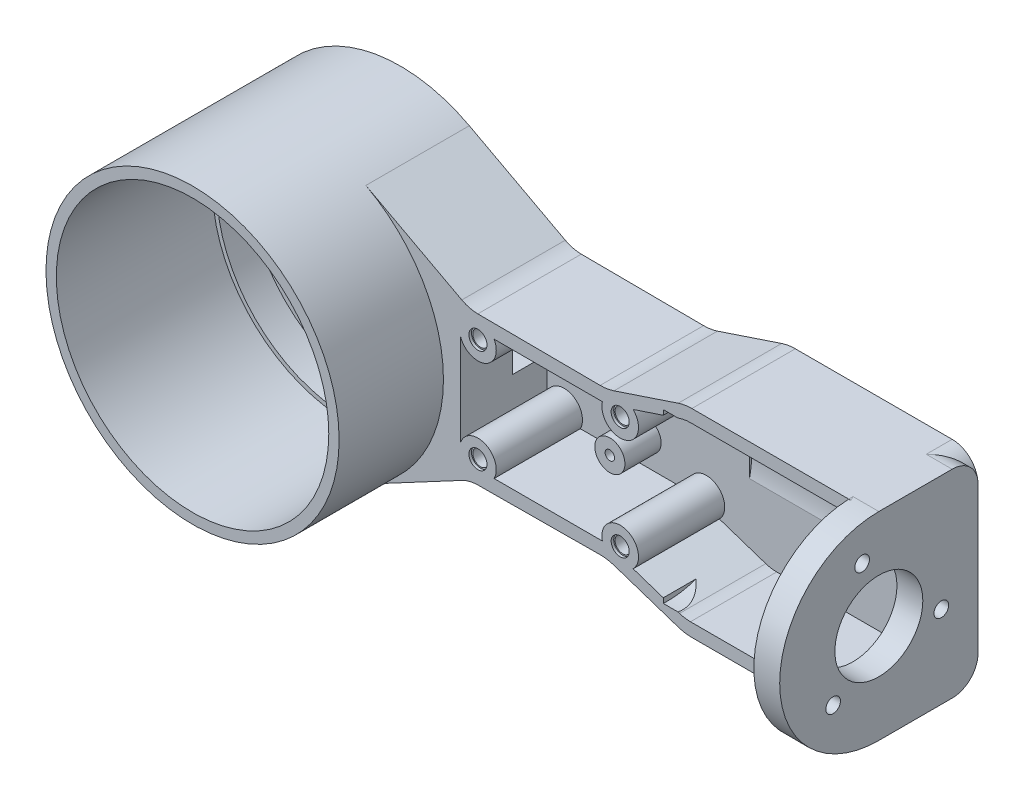
SolidWorks part; units mm, degrees
ref_plane "前视基准面" through (0, 0, 0) normal (0, 0, 1) x (1, 0, 0)
ref_plane "上视基准面" through (0, 0, 0) normal (0, 1, 0) x (1, 0, 0)
ref_plane "右视基准面" through (0, 0, 0) normal (1, 0, 0) x (0, 0, -1)
other "Configuration Table"
sketch "草图1" plane through (0, 0, 0) normal (0, 0, 1) x (1, 0, 0)
  line L0 (16, -30) -> (38.2587, -18.1287)
  line L1 (41.9734, -17.1877) -> (70.3452, -17.0103)
  line L2 (73.5699, -17.5233) -> (88.4605, -22.4868)
  line L3 (91.6228, -23) -> (128, -23)
  line L4 (134, -17) -> (134, 17)
  line L5 (128, 23) -> (91.6228, 23)
  line L6 (88.4605, 22.4868) -> (73.5699, 17.5233)
  line L7 (70.3452, 17.0103) -> (41.9734, 17.1877)
  line L8 (38.2587, 18.1287) -> (16, 30)
  arc A0 (38.2587, -18.1287) -> (41.9734, -17.1877) centre (42.0234, -25.1875) cw
  arc A1 (70.3452, -17.0103) -> (73.5699, -17.5233) centre (70.4077, -27.0101) cw
  arc A2 (88.4605, -22.4868) -> (91.6228, -23) centre (91.6228, -13) ccw
  arc A3 (128, -23) -> (134, -17) centre (128, -17) ccw
  arc A4 (134, 17) -> (128, 23) centre (128, 17) ccw
  arc A5 (91.6228, 23) -> (88.4605, 22.4868) centre (91.6228, 13) ccw
  arc A6 (73.5699, 17.5233) -> (70.3452, 17.0103) centre (70.4077, 27.0101) cw
  arc A7 (41.9734, 17.1877) -> (38.2587, 18.1287) centre (42.0234, 25.1875) cw
  arc A8 (16, 30) -> (16, -30) centre (0, 0) ccw
extrude "Single_flat_print_face_roof_T4" add sketch "草图1" along normal blind 4
ref_plane "Plane_z_4_1" through (0, 0, 4) normal (0, 0, 1) x (1, 0, 0)
sketch "草图2" plane through (0, 0, 4) normal (0, 0, 1) x (1, 0, 0)
  circle A0 centre (0, 0) radius 34
extrude "Motor_roof_total_T5" add sketch "草图2" along normal blind 1
ref_plane "Plane_z_4_2" through (0, 0, 4) normal (0, 0, 1) x (1, 0, 0)
sketch "草图3" plane through (0, 0, 4) normal (0, 0, 1) x (1, 0, 0)
  line L0 (16, -30) -> (38.2587, -18.1287)
  line L1 (41.9734, -17.1877) -> (70.3452, -17.0103)
  line L2 (73.5699, -17.5233) -> (88.4605, -22.4868)
  line L3 (91.6228, -23) -> (128, -23)
  line L4 (134, -17) -> (134, 17)
  line L5 (128, 23) -> (91.6228, 23)
  line L6 (88.4605, 22.4868) -> (73.5699, 17.5233)
  line L7 (70.3452, 17.0103) -> (41.9734, 17.1877)
  line L8 (38.2587, 18.1287) -> (16, 30)
  arc A0 (38.2587, -18.1287) -> (41.9734, -17.1877) centre (42.0234, -25.1875) cw
  arc A1 (70.3452, -17.0103) -> (73.5699, -17.5233) centre (70.4077, -27.0101) cw
  arc A2 (88.4605, -22.4868) -> (91.6228, -23) centre (91.6228, -13) ccw
  arc A3 (128, -23) -> (134, -17) centre (128, -17) ccw
  arc A4 (134, 17) -> (128, 23) centre (128, 17) ccw
  arc A5 (91.6228, 23) -> (88.4605, 22.4868) centre (91.6228, 13) ccw
  arc A6 (73.5699, 17.5233) -> (70.3452, 17.0103) centre (70.4077, 27.0101) cw
  arc A7 (41.9734, 17.1877) -> (38.2587, 18.1287) centre (42.0234, 25.1875) cw
  arc A8 (16, 30) -> (16, -30) centre (0, 0) ccw
extrude "Arm_shell_blank_toZ24" add sketch "草图3" along normal blind 20
ref_plane "Plane_z_24_3" through (0, 0, 24) normal (0, 0, 1) x (1, 0, 0)
sketch "草图4" plane through (0, 0, 24) normal (0, 0, 1) x (1, 0, 0)
  circle A0 centre (0, 0) radius 30.6
extrude "Rotor_cup_ID61p2_roof_T5" cut sketch "草图4" against normal blind 19
ref_plane "Plane_z_24_4" through (0, 0, 24) normal (0, 0, 1) x (1, 0, 0)
sketch "草图5" plane through (0, 0, 24) normal (0, 0, 1) x (1, 0, 0)
  line L0 (41, -14) -> (70.7018, -14)
  line L1 (73.2316, -14.4105) -> (88.7684, -19.5895)
  line L2 (91.2982, -20) -> (125, -20)
  line L3 (128, -17) -> (128, 17)
  line L4 (125, 20) -> (91.2982, 20)
  line L5 (88.7684, 19.5895) -> (73.2316, 14.4105)
  line L6 (70.7018, 14) -> (41, 14)
  line L7 (38, 11) -> (38, -11)
  arc A0 (38, -11) -> (41, -14) centre (41, -11) ccw
  arc A1 (70.7018, -14) -> (73.2316, -14.4105) centre (70.7018, -22) cw
  arc A2 (88.7684, -19.5895) -> (91.2982, -20) centre (91.2982, -12) ccw
  arc A3 (125, -20) -> (128, -17) centre (125, -17) ccw
  arc A4 (128, 17) -> (125, 20) centre (125, 17) ccw
  arc A5 (91.2982, 20) -> (88.7684, 19.5895) centre (91.2982, 12) ccw
  arc A6 (73.2316, 14.4105) -> (70.7018, 14) centre (70.7018, 22) cw
  arc A7 (41, 14) -> (38, 11) centre (41, 11) ccw
extrude "Bottom_service_bay_roof_T4" cut sketch "草图5" against normal blind 20
ref_plane "Plane_z_24_5" through (0, 0, 24) normal (0, 0, 1) x (1, 0, 0)
sketch "草图6" plane through (0, 0, 24) normal (0, 0, 1) x (1, 0, 0)
  circle A0 centre (0, 0) radius 34
  circle A1 centre (0, 0) radius 30.6
extrude "Rotor_wrap_skirt_OD68_toZ48p2" add sketch "草图6" along normal blind 24.2
ref_plane "Plane_z_48.2_6" through (0, 0, 48.2) normal (0, 0, 1) x (1, 0, 0)
sketch "草图7" plane through (0, 0, 48.2) normal (0, 0, 1) x (1, 0, 0)
  circle A0 centre (0, 0) radius 31.6
extrude "Thin_lower_shroud_T2p4_radial_clearance1p8" cut sketch "草图7" against normal blind 36.2
ref_plane "Plane_z_5_7" through (0, 0, 5) normal (0, 0, 1) x (1, 0, 0)
sketch "草图8" plane through (0, 0, 5) normal (0, 0, 1) x (1, 0, 0)
  circle A0 centre (8.8388, 8.8388) radius 5
  circle A1 centre (-8.8388, 8.8388) radius 5
  circle A2 centre (-8.8388, -8.8388) radius 5
  circle A3 centre (8.8388, -8.8388) radius 5
extrude "Four_motor_mount_bosses_toZ12" add sketch "草图8" along normal blind 7
ref_plane "Plane_z_12_8" through (0, 0, 12) normal (0, 0, 1) x (1, 0, 0)
sketch "草图9" plane through (0, 0, 12) normal (0, 0, 1) x (1, 0, 0)
  line L0 (-2, -3) -> (42, -3)
  line L1 (43, -2) -> (43, 2)
  line L2 (42, 3) -> (-2, 3)
  line L3 (-3, 2) -> (-3, -2)
  arc A0 (-3, -2) -> (-2, -3) centre (-2, -2) ccw
  arc A1 (42, -3) -> (43, -2) centre (42, -2) ccw
  arc A2 (43, 2) -> (42, 3) centre (42, 2) ccw
  arc A3 (-2, 3) -> (-3, 2) centre (-2, 2) ccw
extrude "Straight_six_D1_wire_channel_W6_H7" cut sketch "草图9" against normal blind 7
ref_plane "Plane_z_12_9" through (0, 0, 12) normal (0, 0, 1) x (1, 0, 0)
sketch "草图10" plane through (0, 0, 12) normal (0, 0, 1) x (1, 0, 0)
  circle A0 centre (8.8388, 8.8388) radius 1.7
  circle A1 centre (-8.8388, 8.8388) radius 1.7
  circle A2 centre (-8.8388, -8.8388) radius 1.7
  circle A3 centre (8.8388, -8.8388) radius 1.7
extrude "Rotor_4xM3_PCD25" cut sketch "草图10" against normal blind 12
sketch "草图11" plane through (0, 0, 0) normal (0, 0, 1) x (1, 0, 0)
  circle A0 centre (8.8388, 8.8388) radius 3.15
  circle A1 centre (-8.8388, 8.8388) radius 3.15
  circle A2 centre (-8.8388, -8.8388) radius 3.15
  circle A3 centre (8.8388, -8.8388) radius 3.15
extrude "Top_flush_motor_head_recess_D6p3_depth3p6" cut sketch "草图11" along normal blind 3.6
ref_plane "Plane_x_128_11" through (128, 0, 0) normal (1, 0, 0) x (0, 0, -1)
sketch "草图12" plane through (128, 0, 0) normal (1, 0, 0) x (0, 0, -1)
  line L0 (0, -17) -> (0, 17)
  line L1 (-6, 23) -> (-23, 23)
  line L2 (-23, -23) -> (-6, -23)
  arc A0 (0, 17) -> (-6, 23) centre (-6, 17) ccw
  arc A1 (-23, 23) -> (-23, -23) centre (-23, 0) ccw
  arc A2 (-6, -23) -> (0, -17) centre (-6, -17) ccw
extrude "Downward_round_encoder_carrier_T6" add sketch "草图12" along normal blind 6
ref_plane "Plane_y_-23_12" through (0, -23, 0) normal (0, 1, 0) x (1, 0, 0)
sketch "草图13" plane through (0, -23, 0) normal (0, 1, 0) x (1, 0, 0)
  line L0 (106, -4) -> (127, -4)
  line L1 (128, -5) -> (128, -22)
  line L2 (127, -23) -> (122.2235, -23)
  line L3 (121.7977, -22.9048) -> (105.5742, -15.2702)
  line L4 (105, -14.3654) -> (105, -5)
  arc A0 (105, -5) -> (106, -4) centre (106, -5) cw
  arc A1 (127, -4) -> (128, -5) centre (127, -5) cw
  arc A2 (128, -22) -> (127, -23) centre (127, -22) cw
  arc A3 (122.2235, -23) -> (121.7977, -22.9048) centre (122.2235, -22) cw
  arc A4 (105.5742, -15.2702) -> (105, -14.3654) centre (106, -14.3654) cw
extrude "Carrier_web_-23" add sketch "草图13" along normal blind 3
ref_plane "Plane_y_20_13" through (0, 20, 0) normal (0, 1, 0) x (1, 0, 0)
sketch "草图14" plane through (0, 20, 0) normal (0, 1, 0) x (1, 0, 0)
  line L0 (106, -4) -> (127, -4)
  line L1 (128, -5) -> (128, -22)
  line L2 (127, -23) -> (122.2235, -23)
  line L3 (121.7977, -22.9048) -> (105.5742, -15.2702)
  line L4 (105, -14.3654) -> (105, -5)
  arc A0 (105, -5) -> (106, -4) centre (106, -5) cw
  arc A1 (127, -4) -> (128, -5) centre (127, -5) cw
  arc A2 (128, -22) -> (127, -23) centre (127, -22) cw
  arc A3 (122.2235, -23) -> (121.7977, -22.9048) centre (122.2235, -22) cw
  arc A4 (105.5742, -15.2702) -> (105, -14.3654) centre (106, -14.3654) cw
extrude "Carrier_web_20" add sketch "草图14" along normal blind 3
ref_plane "Plane_x_134_14" through (134, 0, 0) normal (1, 0, 0) x (0, 0, -1)
sketch "草图15" plane through (134, 0, 0) normal (1, 0, 0) x (0, 0, -1)
  circle A0 centre (-23, 0) radius 10.2
  circle A1 centre (-33.6066, -10.6066) radius 1.7
  circle A2 centre (-8.5111, -3.8823) radius 1.7
  circle A3 centre (-26.8823, 14.4889) radius 1.7
extrude "Encoder_pilot_and_3M3_rotated_minus45" cut sketch "草图15" against normal blind 6
ref_plane "Plane_x_128_15" through (128, 0, 0) normal (1, 0, 0) x (0, 0, -1)
sketch "草图16" plane through (128, 0, 0) normal (1, 0, 0) x (0, 0, -1)
  circle A0 centre (-23, 0) radius 19.5
extrude "Encoder_body_D39_extended_insertion_relief" cut sketch "草图16" against normal blind 43
ref_plane "Plane_x_110_16" through (110, 0, 0) normal (1, 0, 0) x (0, 0, -1)
sketch "草图17" plane through (110, 0, 0) normal (1, 0, 0) x (0, 0, -1)
  line L0 (-3, 9) -> (-3, 19)
  line L1 (-5, 21) -> (-18, 21)
  line L2 (-20, 19) -> (-20, 9)
  line L3 (-18, 7) -> (-5, 7)
  arc A0 (-5, 7) -> (-3, 9) centre (-5, 9) ccw
  arc A1 (-3, 19) -> (-5, 21) centre (-5, 19) ccw
  arc A2 (-18, 21) -> (-20, 19) centre (-18, 19) ccw
  arc A3 (-20, 9) -> (-18, 7) centre (-18, 9) ccw
extrude "Internal_corner_gland_and_cable_pocket" cut sketch "草图17" against normal blind 18
ref_plane "Plane_z_4_17" through (0, 0, 4) normal (0, 0, 1) x (1, 0, 0)
sketch "草图18" plane through (0, 0, 4) normal (0, 0, 1) x (1, 0, 0)
  circle A0 centre (61, -7.5) radius 3.5
  circle A1 centre (61, 7.5) radius 3.5
extrude "PCB_fixed_to_arm_roof_two_D7_bosses" add sketch "草图18" along normal blind 8.4
ref_plane "Plane_z_12.4_18" through (0, 0, 12.4) normal (0, 0, 1) x (1, 0, 0)
sketch "草图19" plane through (0, 0, 12.4) normal (0, 0, 1) x (1, 0, 0)
  circle A0 centre (61, -7.5) radius 1.1
  circle A1 centre (61, 7.5) radius 1.1
extrude "PCB_standoff_M2_upper_screw_through" cut sketch "草图19" against normal blind 12.4
sketch "草图20" plane through (0, 0, 0) normal (0, 0, 1) x (1, 0, 0)
  circle A0 centre (61, -7.5) radius 2.15
  circle A1 centre (61, 7.5) radius 2.15
extrude "PCB_M2x12_head_recess_flush_print_face" cut sketch "草图20" along normal blind 2.4
ref_plane "Plane_z_4_20" through (0, 0, 4) normal (0, 0, 1) x (1, 0, 0)
sketch "草图21" plane through (0, 0, 4) normal (0, 0, 1) x (1, 0, 0)
  circle A0 centre (42, -12) radius 4.25
  circle A1 centre (42, 12) radius 4.25
  circle A2 centre (75, -13) radius 4.25
  circle A3 centre (75, 13) radius 4.25
extrude "Bottom_cover_four_heatset_bosses" add sketch "草图21" along normal blind 20
ref_plane "Plane_z_24_21" through (0, 0, 24) normal (0, 0, 1) x (1, 0, 0)
sketch "草图22" plane through (0, 0, 24) normal (0, 0, 1) x (1, 0, 0)
  circle A0 centre (42, -12) radius 1.8
  circle A1 centre (42, 12) radius 1.8
  circle A2 centre (75, -13) radius 1.8
  circle A3 centre (75, 13) radius 1.8
extrude "M3_OD4_L5_heatset_pilot_D3p6_depth5p4" cut sketch "草图22" against normal blind 5.4
ref_plane "Plane_z_24_22" through (0, 0, 24) normal (0, 0, 1) x (1, 0, 0)
sketch "草图23" plane through (0, 0, 24) normal (0, 0, 1) x (1, 0, 0)
  circle A0 centre (42, -12) radius 2.1
  circle A1 centre (42, 12) radius 2.1
  circle A2 centre (75, -13) radius 2.1
  circle A3 centre (75, 13) radius 2.1
extrude "M3_OD4_heatset_leadin_D4p2" cut sketch "草图23" against normal blind 0.6
ref_plane "Plane_z_18.6_23" through (0, 0, 18.6) normal (0, 0, 1) x (1, 0, 0)
sketch "草图24" plane through (0, 0, 18.6) normal (0, 0, 1) x (1, 0, 0)
  circle A0 centre (42, -12) radius 1.7
  circle A1 centre (42, 12) radius 1.7
  circle A2 centre (75, -13) radius 1.7
  circle A3 centre (75, 13) radius 1.7
extrude "M3_screw_tip_relief" cut sketch "草图24" against normal blind 2.6
